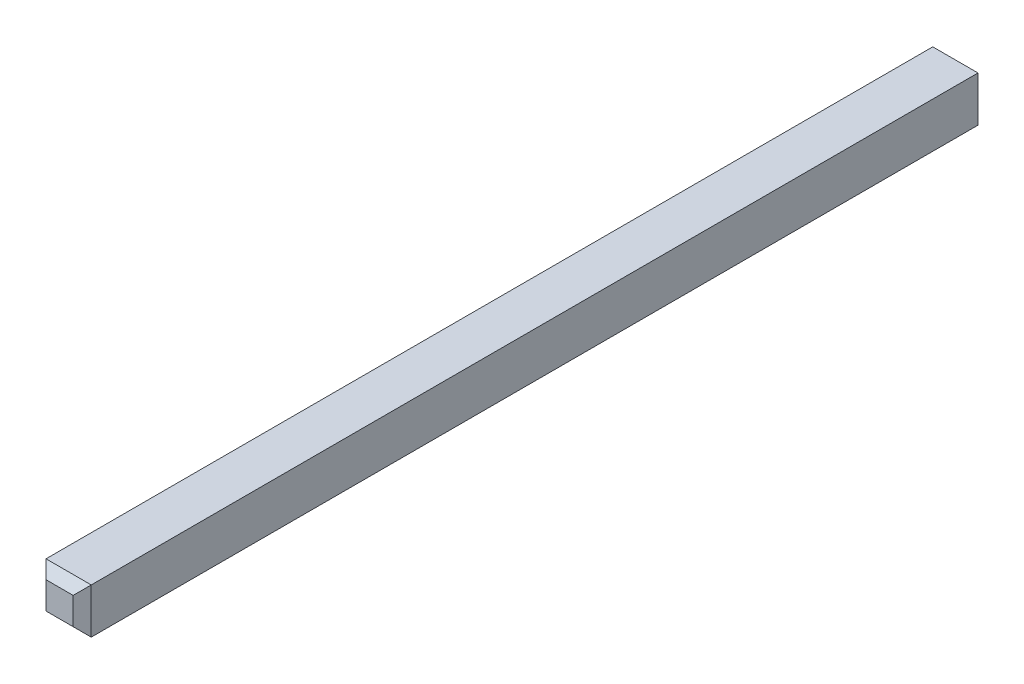
SolidWorks part; units mm, degrees
ref_plane "前视基准面" through (0, 0, 0) normal (0, 0, 1) x (1, 0, 0)
ref_plane "上视基准面" through (0, 0, 0) normal (0, 1, 0) x (1, 0, 0)
ref_plane "右视基准面" through (0, 0, 0) normal (1, 0, 0) x (0, 0, -1)
sketch "草图1" plane through (0, 0, 0) normal (0, 0, 1) x (1, 0, 0)
  line L1 (-0.25, 0.25) -> (0.25, 0.25)
  line L2 (-0.25, 0.25) -> (-0.25, -0.25)
  line L3 (-0.25, -0.25) -> (0.25, -0.25)
  line L4 (0.25, 0.25) -> (0.25, -0.25)
  line L5 (-0.25, 0.25) -> (0.25, -0.25) construction
  line L6 (-0.25, -0.25) -> (0.25, 0.25) construction
  circle A0 centre (0, 0) radius 0.3536 construction
  point P0 (0, 0)
extrude "凸台-拉伸1" add sketch "草图1" along normal blind 10
chamfer "倒角1" distance 0.1 angle 45 8 edges at (0, -0.25, 10) (-0.25, 0, 10) (0, 0.25, 10) (0.25, 0, 10) (0, 0.25, 0) (-0.25, 0, 0) (0, -0.25, 0) (0.25, 0, 0)
